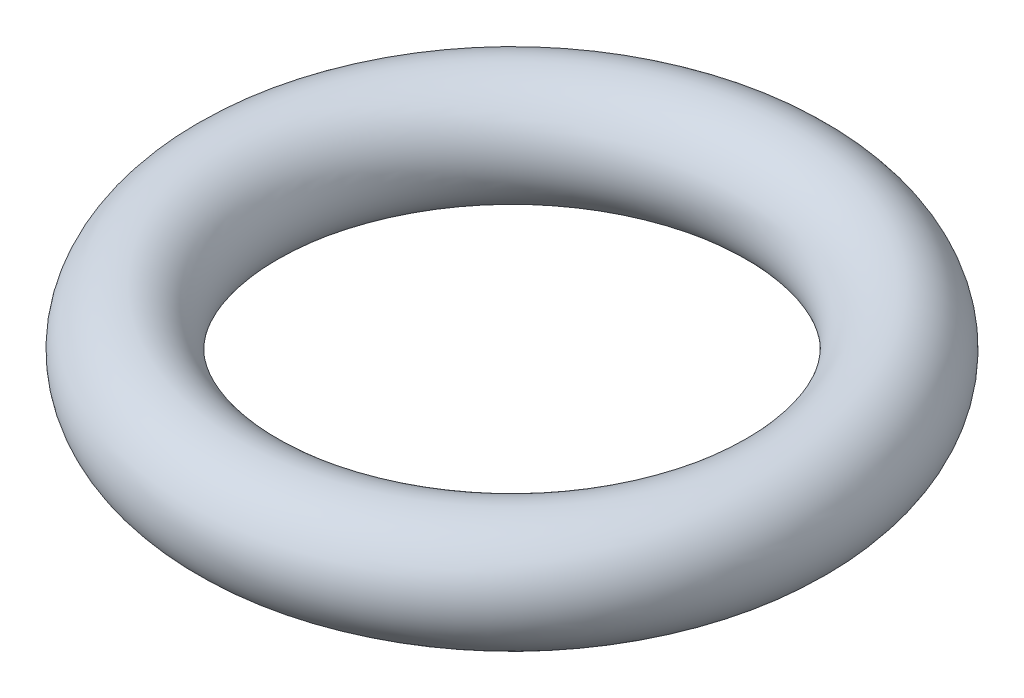
SolidWorks part; units mm, degrees
material "Silicon"
ref_plane "Ön Düzlem" through (0, 0, 0) normal (0, 0, 1) x (1, 0, 0)
ref_plane "Üst Düzlem" through (0, 0, 0) normal (0, 1, 0) x (1, 0, 0)
ref_plane "Sağ Düzlem" through (0, 0, 0) normal (1, 0, 0) x (0, 0, -1)
sketch "Sketch1" plane through (0, 0, 0) normal (0, 1, 0) x (1, 0, 0)
  circle A0 centre (0, 0) radius 3.925
  dimension "D1" = 7.85
sketch "Sketch2" plane through (0, 0, 0) normal (0, 0, 1) x (1, 0, 0)
  line L0 (3.925, 0) -> (-3.925, 0) construction
  circle A0 centre (3.925, 0) radius 0.8
  dimension "D2" = 1.6
  dimension "D1" = 3.925
sweep "Sweep1" add profiles "Sketch2" path "Sketch1"
ref_plane "Plane1" through (0, -0.8, 0) normal (0, 1, 0) x (1, 0, 0)
sketch "Sketch3" plane through (0, -0.8, 0) normal (0, 1, 0) x (1, 0, 0)
  circle A0 centre (0, 0) radius 3.925 construction
  circle A1 centre (0, 0) radius 3.925 construction
